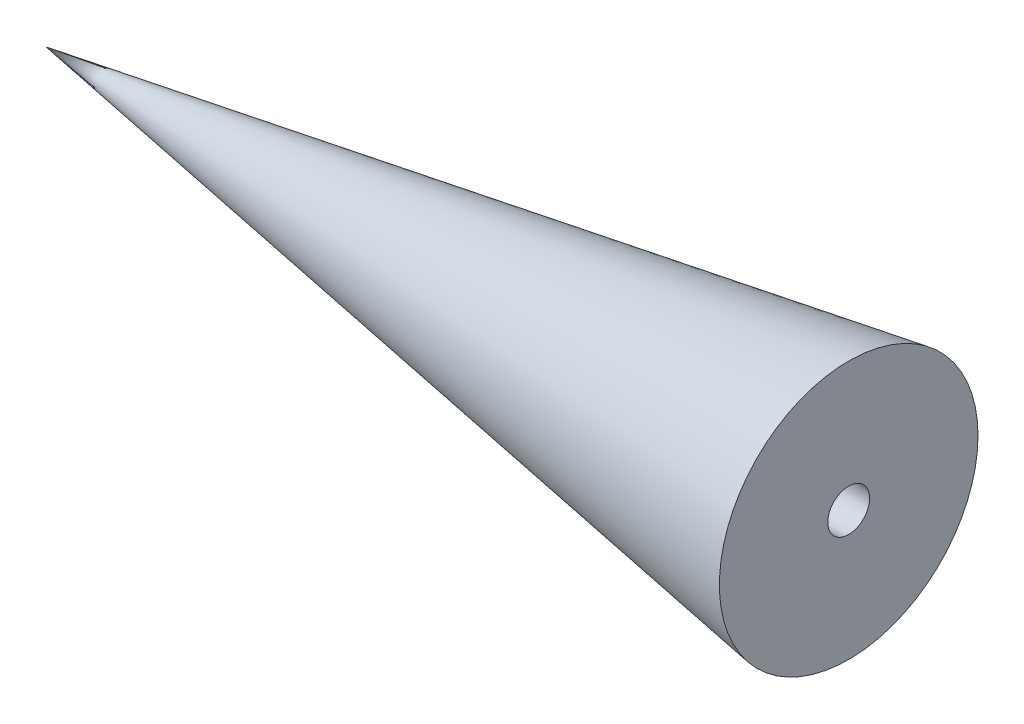
SolidWorks part; units mm, degrees
material "6063-T6"
ref_plane "Płaszczyzna przednia" through (0, 0, 0) normal (0, 0, 1) x (1, 0, 0)
ref_plane "Płaszczyzna górna" through (0, 0, 0) normal (0, 1, 0) x (1, 0, 0)
ref_plane "Płaszczyzna prawa" through (0, 0, 0) normal (1, 0, 0) x (0, 0, -1)
sketch "Sketch1" plane through (0, 0, 0) normal (0, 0, 1) x (1, 0, 0)
  line L1 (0, 0) -> (0, 18.525)
  line L2 (0, 18.525) -> (-115, 0)
  line L3 (0, 0) -> (-115, 0) construction
  line L4 (0, 0) -> (-115, 0)
  dimension "D1" = 115
  dimension "D2" = 18.525
revolve "Revolve1" add sketch "Sketch1" angle 360 about L3
sketch "Sketch2" plane through (0, 0, 0) normal (1, 0, 0) x (0, 0, -1)
  circle A0 centre (0, 0) radius 3
  dimension "D1" = 6
extrude "Cut-Extrude1" cut sketch "Sketch2" against normal blind 50
